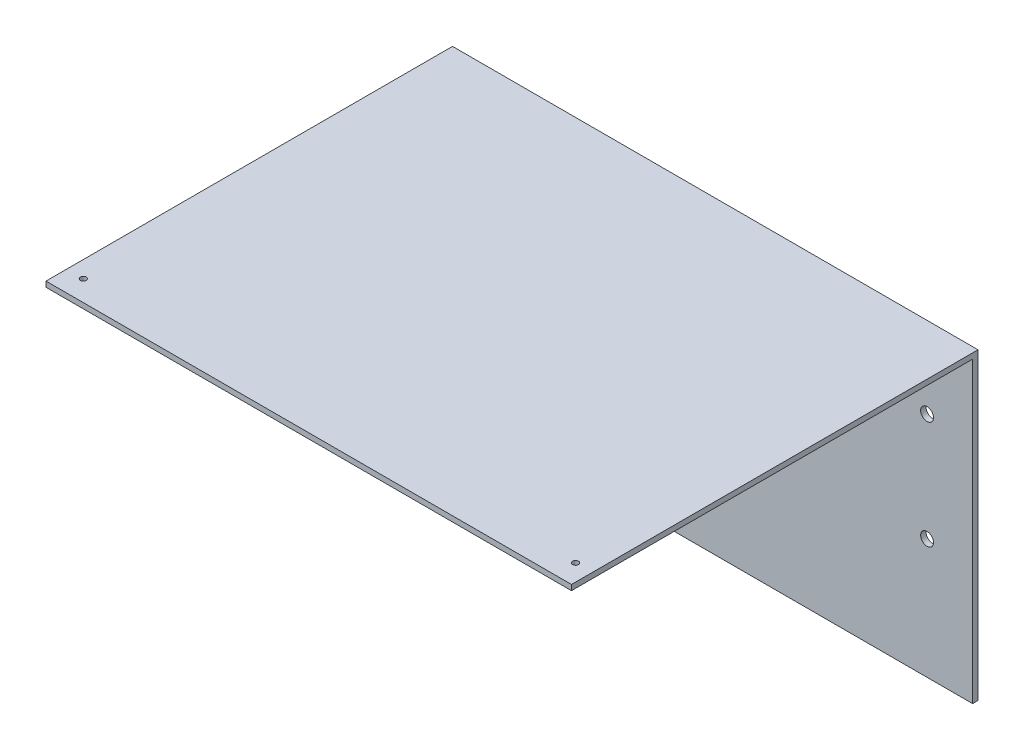
SolidWorks part; units mm, degrees
material "Ti-5Al-2.5Sn Annealed (SS)"
ref_plane "Front Plane" through (0, 0, 0) normal (0, 0, 1) x (1, 0, 0)
ref_plane "Top Plane" through (0, 0, 0) normal (0, 1, 0) x (1, 0, 0)
ref_plane "Right Plane" through (0, 0, 0) normal (1, 0, 0) x (0, 0, -1)
sketch "Sketch1" plane through (0, 0, 0) normal (0, 0, 1) x (1, 0, 0)
  line L1 (0, 0) -> (291.5, 0)
  line L2 (0, 0) -> (0, -168.5)
  line L3 (0, -168.5) -> (291.5, -168.5)
  line L4 (291.5, 0) -> (291.5, -168.5)
  dimension "D1" = 291.5
  dimension "D2" = 168.5
extrude "Boss-Extrude1" add sketch "Sketch1" along normal blind 3
sketch "Sketch2" plane through (0, 0, 3) normal (0, 0, 1) x (1, 0, 0)
  line L0 (145.75, 0) -> (145.75, -168.5) construction
  line L1 (291.5, 0) -> (0, 0) construction
  line L2 (0, -168.5) -> (291.5, -168.5) construction
  point P6 (25.25, -42)
  point P7 (25.25, -102)
  point P11 (266.25, -102)
  point P12 (266.25, -42)
  dimension "D1" = 120.5
  dimension "D2" = 42
  dimension "D3" = 60
hole_wizard "1/4 Clearance Hole1" positions "Sketch3" profile "Sketch4" hole size "1/4" standard "ANSI Inch" end condition up to next
sketch "Sketch3" plane through (0, 0, 3) normal (0, 0, 1) x (1, 0, 0)
  point P0 (25.25, -102)
  point P3 (25.25, -42)
  point P6 (266.25, -42)
  point P9 (266.25, -102)
sketch "Sketch4" plane through (25.25, -102, 3) normal (1, 0, 0) x (0, -1, 0)
  line L0 (0, 0) -> (0, 3)
  line L1 (0, 3) -> (3.5712, 3)
  line L2 (3.5712, 3) -> (3.5712, 0)
  line L5 (3.5712, 0) -> (0, 0)
  line L11 (0, -6.35) -> (0, 107.95) construction
  dimension "Thru Hole Dia." = 7.1425
  dimension "Thru Hole Depth" = 3
sketch "Sketch6" plane through (0, 0, 3) normal (0, 0, 1) x (1, 0, 0)
  line L0 (291.5, -168.5) -> (291.5, 0) construction
  line L1 (0, 0) -> (291.5, 0)
  line L2 (0, 0) -> (0, -3)
  line L3 (0, -3) -> (291.5, -3)
  line L4 (291.5, 0) -> (291.5, -3)
  dimension "D1" = 3
extrude "Boss-Extrude2" add sketch "Sketch6" along normal blind 222.5
sketch "Sketch7" plane through (0, 0, 0) normal (0, 1, 0) x (1, 0, 0)
  line L0 (145.75, 0) -> (145.75, -225.5) construction
  line L1 (291.5, 0) -> (0, 0) construction
  line L2 (291.5, -225.5) -> (0, -225.5) construction
  point P0 (9.25, -214)
  point P7 (282.25, -214)
  dimension "D1" = 136.5
  dimension "D2" = 11.5
hole_wizard "Tap Drill for M4 Tap2" positions "Sketch7" profile "Sketch8" hole size "M4" standard "ISO" end condition up to next
sketch "Sketch8" plane through (9.25, 0, 214) normal (1, 0, 0) x (0, 0, 1)
  line L0 (0, 0) -> (0, 3)
  line L1 (0, 3) -> (1.65, 3)
  line L2 (1.65, 3) -> (1.65, 0)
  line L5 (1.65, 0) -> (0, 0)
  line L11 (0, -6.35) -> (0, 107.95) construction
  dimension "Thru Hole Dia." = 3.3
  dimension "Thru Hole Depth" = 3
